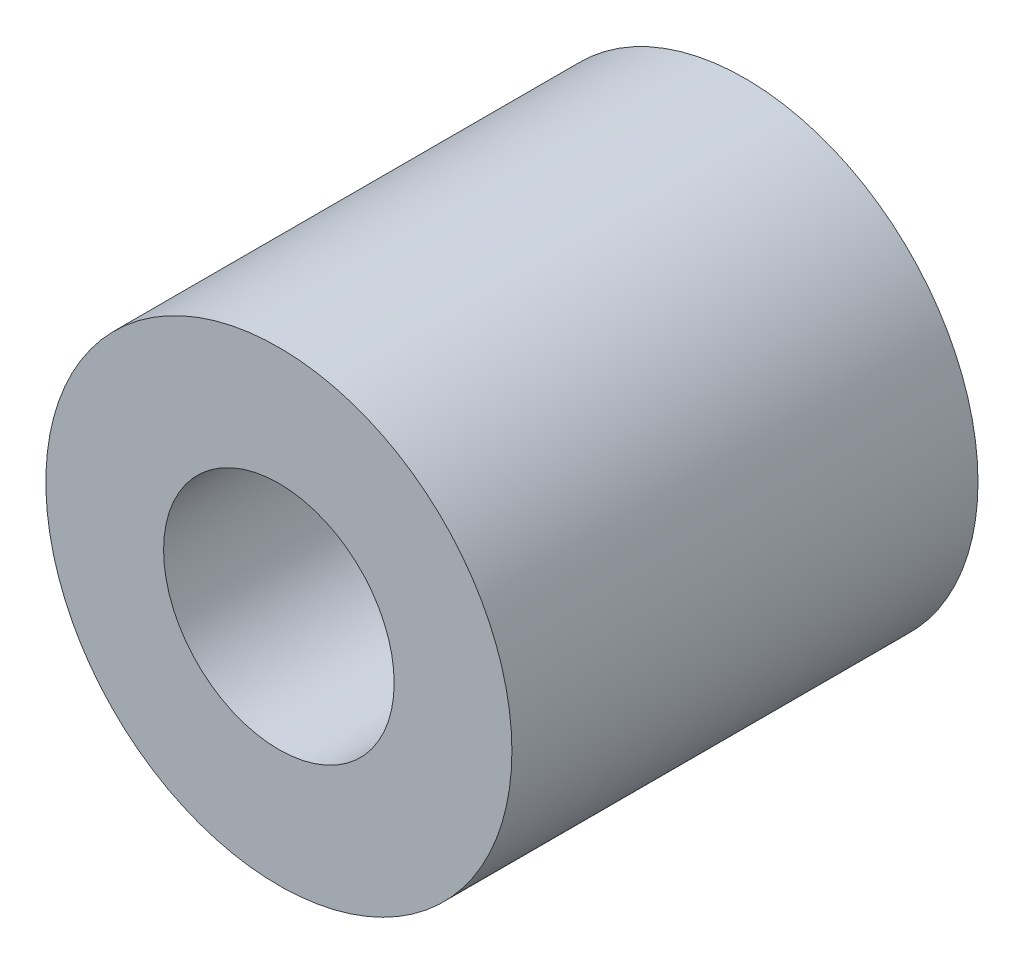
SolidWorks part; units mm, degrees
other "Defeature"
material "Nylon"
ref_plane "Front Plane" through (0, 0, 0) normal (0, 0, 1) x (1, 0, 0)
ref_plane "Top Plane" through (0, 0, 0) normal (0, 1, 0) x (1, 0, 0)
ref_plane "Right Plane" through (0, 0, 0) normal (1, 0, 0) x (0, 0, -1)
sketch "Sketch1" plane through (0, 0, 0) normal (0, 0, 1) x (1, 0, 0)
  circle A0 centre (0, 0) radius 4.75
  dimension "D1" = 9.5
extrude "Boss-Extrude1" add sketch "Sketch1" against normal mid plane 9.5
sketch "Sketch2" plane through (0, 0, 4.75) normal (0, 0, 1) x (1, 0, 0)
  circle A0 centre (0, 0) radius 2.35
  dimension "D1" = 4.7
extrude "Cut-Extrude1" cut sketch "Sketch2" against normal through all
